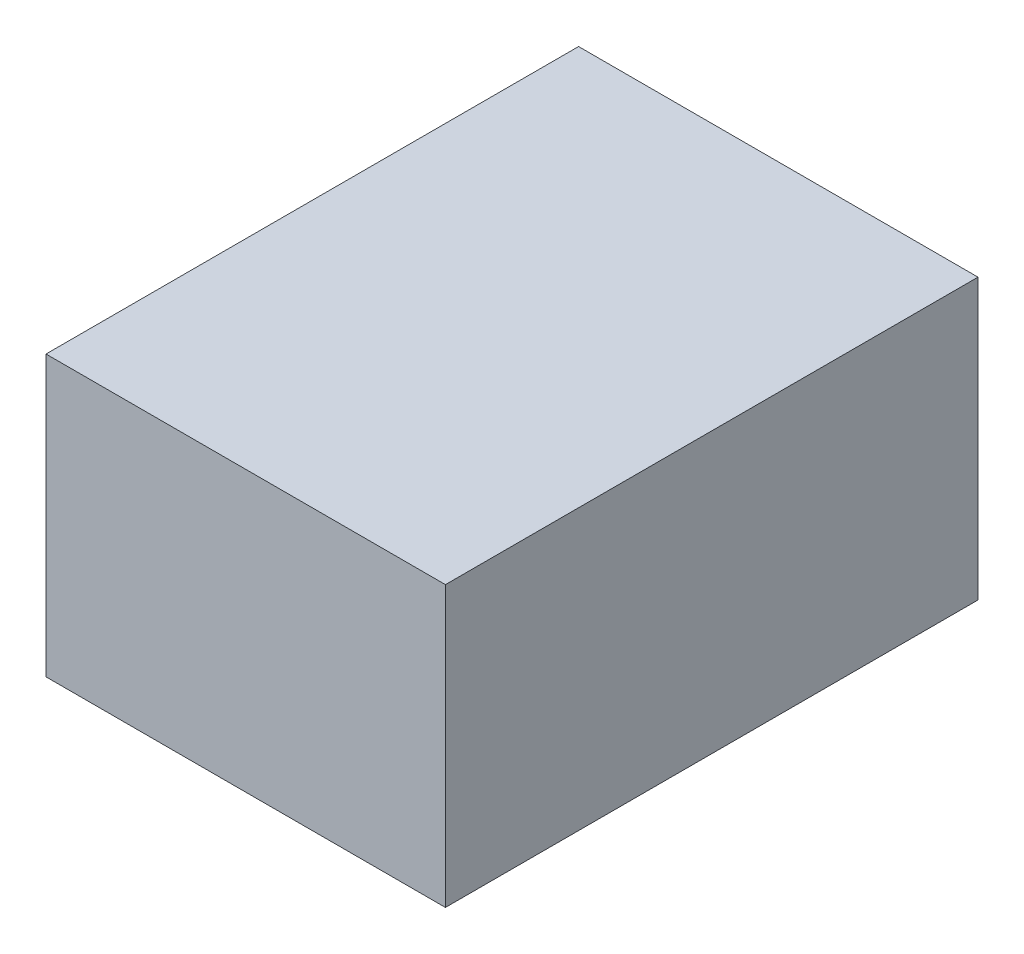
SolidWorks part; units mm, degrees
ref_plane "Front Plane" through (0, 0, 0) normal (0, 0, 1) x (1, 0, 0)
ref_plane "Top Plane" through (0, 0, 0) normal (0, 1, 0) x (1, 0, 0)
ref_plane "Right Plane" through (0, 0, 0) normal (1, 0, 0) x (0, 0, -1)
sketch "Sketch1" plane through (0, 0, 0) normal (0, 0, 1) x (1, 0, 0)
  line L1 (-3.3354, 5.2352) -> (4.2846, 5.2352)
  line L2 (-3.3354, 5.2352) -> (-3.3354, -0.0988)
  line L3 (-3.3354, -0.0988) -> (4.2846, -0.0988)
  line L4 (4.2846, 5.2352) -> (4.2846, -0.0988)
  dimension "D1" = 7.62
  dimension "D2" = 5.334
extrude "Boss-Extrude1" add sketch "Sketch1" along normal blind 10.16
